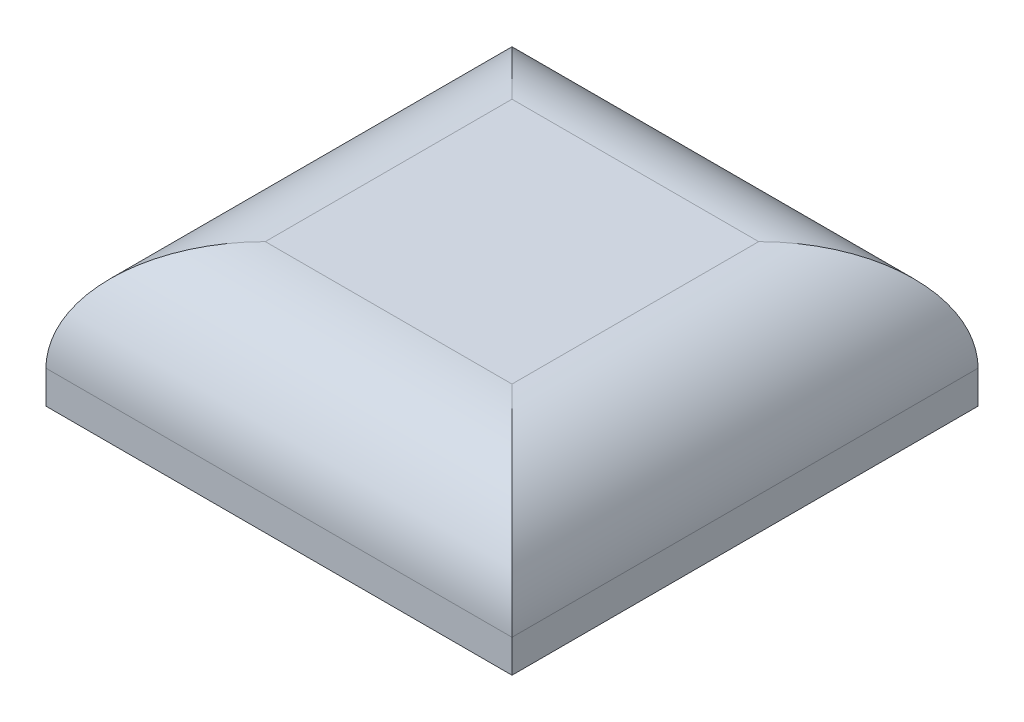
SolidWorks part; units mm, degrees
ref_plane "Front Plane" through (0, 0, 0) normal (0, 0, 1) x (1, 0, 0)
ref_plane "Top Plane" through (0, 0, 0) normal (0, 1, 0) x (1, 0, 0)
ref_plane "Right Plane" through (0, 0, 0) normal (1, 0, 0) x (0, 0, -1)
sketch "Sketch1" plane through (0, 0, 0) normal (0, 1, 0) x (1, 0, 0)
  line L1 (-21.25, -21.25) -> (21.25, -21.25)
  line L2 (-21.25, -21.25) -> (-21.25, 21.25)
  line L3 (-21.25, 21.25) -> (21.25, 21.25)
  line L4 (21.25, -21.25) -> (21.25, 21.25)
  line L5 (-21.25, -21.25) -> (21.25, 21.25) construction
  line L6 (-21.25, 21.25) -> (21.25, -21.25) construction
  point P0 (0, 0)
  dimension "D1" = 42.5
  dimension "D2" = 42.5
extrude "Boss-Extrude1" add sketch "Sketch1" along normal blind 13
fillet "Fillet1" radius 10 4 edges at (0, 13, 21.25) (-21.25, 13, 0) (0, 13, -21.25) (21.25, 13, 0)
